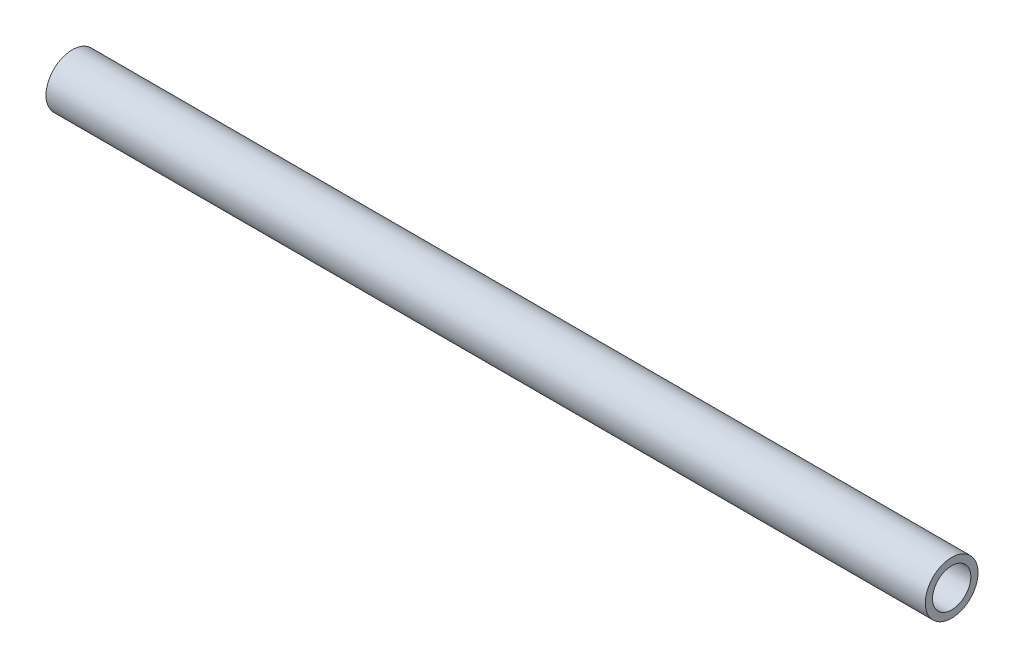
SolidWorks part; units mm, degrees
ref_plane "Front Plane" through (0, 0, 0) normal (0, 0, 1) x (1, 0, 0)
ref_plane "Top Plane" through (0, 0, 0) normal (0, 1, 0) x (1, 0, 0)
ref_plane "Right Plane" through (0, 0, 0) normal (1, 0, 0) x (0, 0, -1)
sketch "Sketch1" plane through (0, 0, 0) normal (1, 0, 0) x (0, 0, -1)
  circle A0 centre (0, 0) radius 13.15
  circle A1 centre (0, 0) radius 9.55
  dimension "D1" = 26.3
  dimension "D2" = 19.1
extrude "Boss-Extrude1" add sketch "Sketch1" along normal blind 438.4
